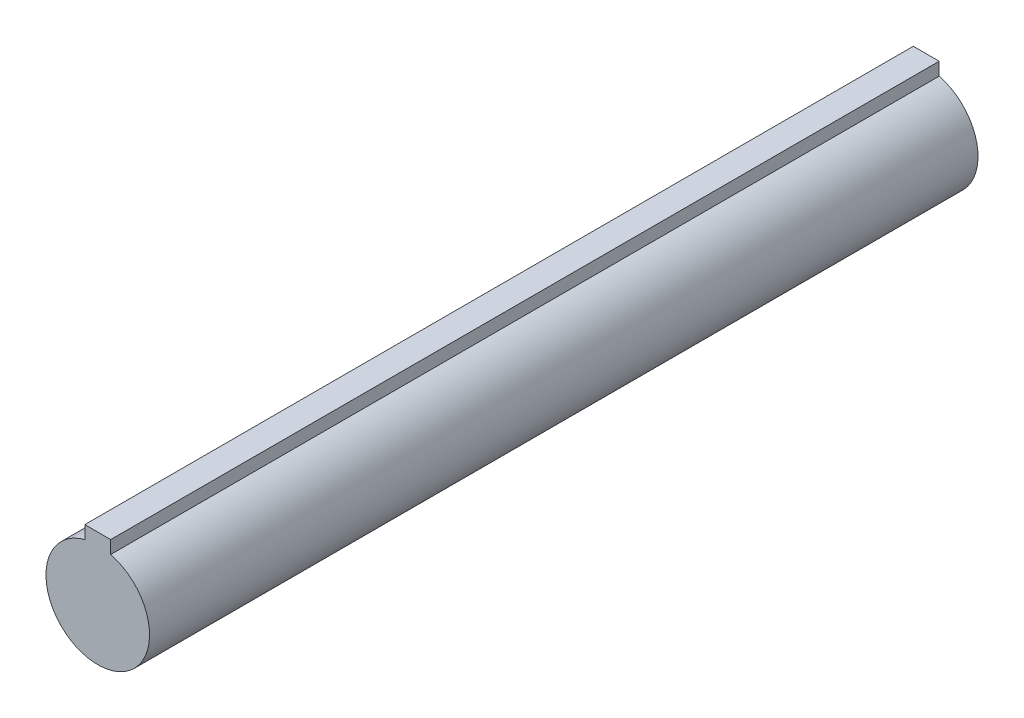
SolidWorks part; units mm, degrees
ref_plane "Front Plane" through (0, 0, 0) normal (0, 0, 1) x (1, 0, 0)
ref_plane "Top Plane" through (0, 0, 0) normal (0, 1, 0) x (1, 0, 0)
ref_plane "Right Plane" through (0, 0, 0) normal (1, 0, 0) x (0, 0, -1)
sketch "Sketch1" plane through (0, 0, 0) normal (0, 0, 1) x (1, 0, 0)
  line L0 (-1.5875, 6.1484) -> (-1.5875, 7.7359)
  line L1 (-1.5875, 7.7359) -> (1.5875, 7.7359)
  line L2 (1.5875, 7.7359) -> (1.5875, 6.1484)
  arc A0 (-1.5875, 6.1484) -> (1.5875, 6.1484) centre (0, 0) ccw
  point P1 (0, 0)
  point P5 (0, 7.7359)
  point P8 (0, 0)
  point P9 (-1.5875, 6.1338)
  dimension "D1" = 12.7
  dimension "D2" = 3.175
  dimension "D3" = 1.5875
extrude "Boss-Extrude1" add sketch "Sketch1" along normal blind 101.6
